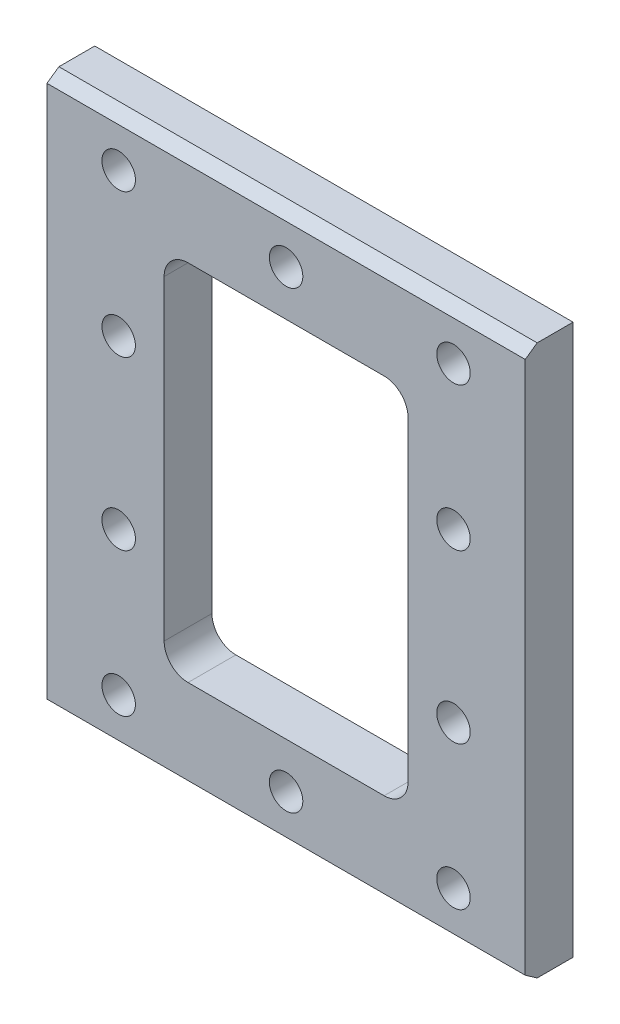
SolidWorks part; units mm, degrees
ref_plane "前视基准面" through (0, 0, 0) normal (0, 0, 1) x (1, 0, 0)
ref_plane "上视基准面" through (0, 0, 0) normal (0, 1, 0) x (1, 0, 0)
ref_plane "右视基准面" through (0, 0, 0) normal (1, 0, 0) x (0, 0, -1)
sketch "草图1" plane through (0, 0, 0) normal (0, 0, 1) x (1, 0, 0)
  line L1 (-100, 115) -> (100, 115)
  line L2 (-100, 115) -> (-100, -115)
  line L3 (-100, -115) -> (100, -115)
  line L4 (100, 115) -> (100, -115)
  line L5 (-100, 115) -> (100, -115) construction
  line L6 (-100, -115) -> (100, 115) construction
  point P0 (0, 0)
  dimension "D1" = 200
  dimension "D2" = 230
extrude "凸台-拉伸1" add sketch "草图1" along normal blind 20
sketch "草图2" plane through (0, 0, 20) normal (0, 0, 1) x (1, 0, 0)
  line L0 (0, 0) -> (-148.4114, 0) construction
  line L1 (-41, 76) -> (41, 76)
  line L2 (-51, 66) -> (-51, -66)
  line L3 (-41, -76) -> (41, -76)
  line L4 (51, 66) -> (51, -66)
  line L5 (-51, 76) -> (51, -76) construction
  line L6 (-51, -76) -> (51, 76) construction
  line L7 (100, 115) -> (-100, 115) construction
  line L8 (-100, 115) -> (-100, -115) construction
  arc A0 (-51, -66) -> (-41, -76) centre (-41, -66) ccw
  arc A1 (41, -76) -> (51, -66) centre (41, -66) ccw
  arc A2 (41, 76) -> (51, 66) centre (41, 66) cw
  arc A3 (-41, 76) -> (-51, 66) centre (-41, 66) ccw
  circle A4 centre (-70, 95) radius 7
  circle A5 centre (0, 95) radius 7
  circle A6 centre (70, 95) radius 7
  circle A7 centre (-70, 35) radius 7
  circle A8 centre (70, 35) radius 7
  circle A9 centre (-70, -35) radius 7
  circle A10 centre (0, -95) radius 7
  circle A11 centre (-70, -95) radius 7
  circle A12 centre (70, -35) radius 7
  circle A13 centre (70, -95) radius 7
  point P0 (0, 0)
  dimension "D3" = 10
  dimension "D4" = 20
  dimension "D5" = 60
  dimension "D6" = 14
  dimension "D7" = 14
  dimension "D8" = 14
  dimension "D9" = 14
  dimension "D10" = 14
  dimension "D11" = 70
  dimension "D12" = 70
  dimension "D13" = 30
  dimension "D1" = 152
  dimension "D2" = 102
extrude "切除-拉伸1" cut sketch "草图2" against normal up to next
chamfer "倒角1" distance 5 angle 35 2 edges at (0, -115, 20) (0, 115, 20)
